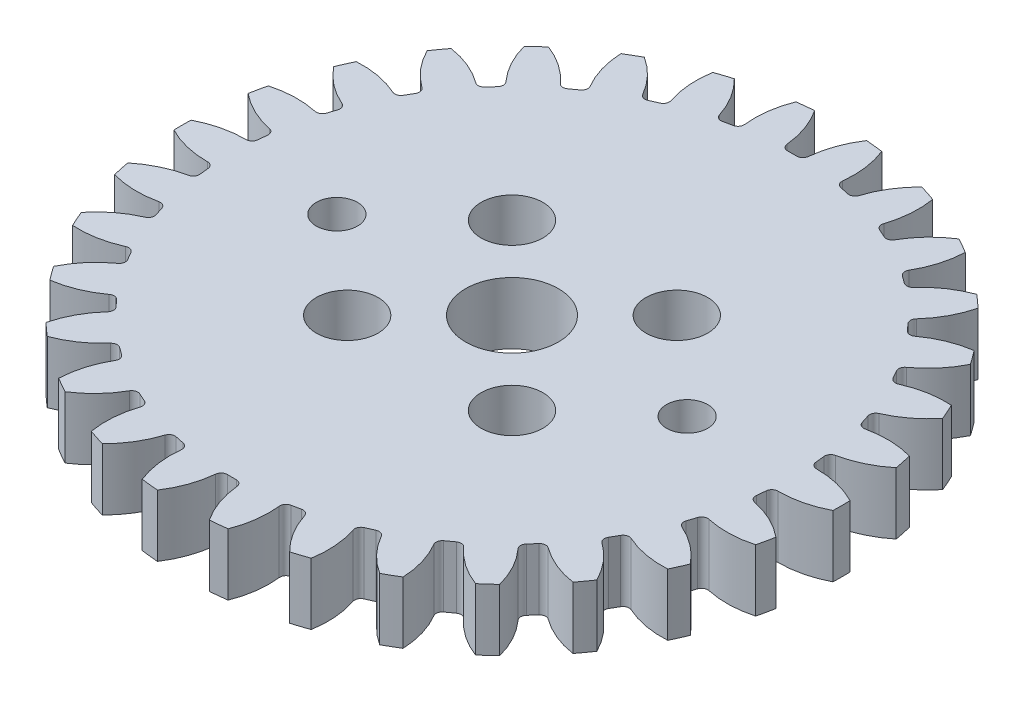
SolidWorks part; units mm, degrees
ref_plane "Alzado" through (0, 0, 0) normal (0, 0, 1) x (1, 0, 0)
ref_plane "Planta" through (0, 0, 0) normal (0, 1, 0) x (1, 0, 0)
ref_plane "Vista lateral" through (0, 0, 0) normal (1, 0, 0) x (0, 0, -1)
sketch "Croquis1" plane through (0, 0, 0) normal (0, 1, 0) x (1, 0, 0)
  line L0 (0, 0) -> (0, 24.4895) construction
  line L1 (-0.2199, 13.6) -> (0.2199, 13.6)
  line L2 (2.6125, 13.3485) -> (3.0427, 13.2571)
  line L3 (5.3308, 12.5136) -> (5.7325, 12.3348)
  line L4 (7.816, 11.1319) -> (8.1718, 10.8734)
  line L5 (9.9596, 9.2636) -> (10.2539, 8.9368)
  line L6 (11.668, 6.9904) -> (11.8879, 6.6096)
  line L7 (12.8664, 4.4117) -> (13.0023, 3.9935)
  line L8 (13.5025, 1.6403) -> (13.5485, 1.2029)
  line L9 (13.5485, -1.2029) -> (13.5025, -1.6403)
  line L10 (13.0023, -3.9935) -> (12.8664, -4.4117)
  line L11 (11.8879, -6.6096) -> (11.668, -6.9904)
  line L12 (10.2539, -8.9368) -> (9.9596, -9.2636)
  line L13 (8.1718, -10.8734) -> (7.816, -11.1319)
  line L14 (5.7325, -12.3348) -> (5.3308, -12.5136)
  line L15 (3.0427, -13.2571) -> (2.6125, -13.3485)
  line L16 (0.2199, -13.6) -> (-0.2199, -13.6)
  line L17 (-2.6125, -13.3485) -> (-3.0427, -13.2571)
  line L18 (-5.3308, -12.5136) -> (-5.7325, -12.3348)
  line L19 (-7.816, -11.1319) -> (-8.1718, -10.8734)
  line L20 (-9.9596, -9.2636) -> (-10.2539, -8.9368)
  line L21 (-11.668, -6.9904) -> (-11.8879, -6.6096)
  line L22 (-12.8664, -4.4117) -> (-13.0023, -3.9935)
  line L23 (-13.5025, -1.6403) -> (-13.5485, -1.2029)
  line L24 (-13.5485, 1.2029) -> (-13.5025, 1.6403)
  line L25 (-13.0023, 3.9935) -> (-12.8664, 4.4117)
  line L26 (-11.8879, 6.6096) -> (-11.668, 6.9904)
  line L27 (-10.2539, 8.9368) -> (-9.9596, 9.2636)
  line L28 (-8.1718, 10.8734) -> (-7.816, 11.1319)
  line L29 (-5.7325, 12.3348) -> (-5.3308, 12.5136)
  line L30 (-3.0427, 13.2571) -> (-2.6125, 13.3485)
  line L31 (0, 0) -> (0, -0.9994) construction
  line L32 (0, 0) -> (10.2539, 0) construction
  circle A0 centre (0, 0) radius 16
  arc A1 (0.5184, 13.8707) -> (2.08, 16.88) centre (5.0567, 13.4256) cw
  arc A2 (-0.5184, 13.8707) -> (-2.08, 16.88) centre (-5.0567, 13.4256) ccw
  arc A3 (-2.08, 16.88) -> (2.08, 16.88) centre (0, -0.9994) cw
  arc A4 (0.2199, 13.6) -> (0.5184, 13.8707) centre (0.2199, 13.9) ccw
  arc A5 (-0.5184, 13.8707) -> (-0.2199, 13.6) centre (-0.2199, 13.9) ccw
  arc A6 (1.475, 16.9436) -> (5.5441, 16.0787) centre (-0.2078, -0.9776) cw
  arc A7 (3.391, 13.4598) -> (5.5441, 16.0787) centre (7.7375, 12.0809) cw
  arc A8 (3.0427, 13.2571) -> (3.391, 13.4598) centre (3.105, 13.5505) ccw
  arc A9 (2.3768, 13.6754) -> (2.6125, 13.3485) centre (2.6749, 13.642) ccw
  arc A10 (2.3768, 13.6754) -> (1.475, 16.9436) centre (-2.1548, 14.1835) ccw
  arc A11 (4.9655, 16.2667) -> (8.7659, 14.5746) centre (-0.4065, -0.913) cw
  arc A12 (6.1153, 12.4607) -> (8.7659, 14.5746) centre (10.0802, 10.2081) cw
  arc A13 (5.7325, 12.3348) -> (6.1153, 12.4607) centre (5.8545, 12.6089) ccw
  arc A14 (5.1681, 12.8824) -> (5.3308, 12.5136) centre (5.4528, 12.7877) ccw
  arc A15 (5.1681, 12.8824) -> (4.9655, 16.2667) centre (0.8412, 14.3216) ccw
  arc A16 (8.2391, 14.8788) -> (11.6046, 12.4336) centre (-0.5874, -0.8085) cw
  arc A17 (8.5724, 10.9169) -> (11.6046, 12.4336) centre (11.9823, 7.8893) cw
  arc A18 (8.1718, 10.8734) -> (8.5724, 10.9169) centre (8.3481, 11.1161) ccw
  arc A19 (7.7336, 11.5264) -> (7.816, 11.1319) centre (7.9923, 11.3746) ccw
  arc A20 (7.7336, 11.5264) -> (8.2391, 14.8788) centre (3.8004, 13.8337) ccw
  arc A21 (11.1525, 12.8407) -> (13.9361, 9.7492) centre (-0.7427, -0.6687) cw
  arc A22 (10.6549, 8.896) -> (13.9361, 9.7492) centre (13.3607, 5.2256) cw
  arc A23 (10.2539, 8.9368) -> (10.6549, 8.896) centre (10.4768, 9.1375) ccw
  arc A24 (9.961, 9.6666) -> (9.9596, 9.2636) centre (10.1826, 9.4643) ccw
  arc A25 (9.961, 9.6666) -> (11.1525, 12.8407) centre (6.5936, 12.7413) ccw
  arc A26 (13.5785, 10.2413) -> (15.6585, 6.6387) centre (-0.8655, -0.4997) cw
  arc A27 (12.2716, 6.4864) -> (15.6585, 6.6387) centre (14.1552, 2.3336) cw
  arc A28 (11.8879, 6.6096) -> (12.2716, 6.4864) centre (12.1477, 6.7596) ccw
  arc A29 (11.7532, 7.3843) -> (11.668, 6.9904) centre (11.9278, 7.1404) ccw
  arc A30 (11.7532, 7.3843) -> (13.5785, 10.2413) centre (9.0986, 11.092) ccw
  arc A31 (15.4111, 7.1944) -> (16.6966, 3.238) centre (-0.9505, -0.3088) cw
  arc A32 (13.352, 3.7932) -> (16.6966, 3.238) centre (14.3311, -0.6604) cw
  arc A33 (13.0023, 3.9935) -> (13.352, 3.7932) centre (13.2876, 4.0862) ccw
  arc A34 (13.0316, 4.7794) -> (12.8664, 4.4117) centre (13.1517, 4.5044) ccw
  arc A35 (13.0316, 4.7794) -> (15.4111, 7.1944) centre (11.2059, 8.9579) ccw
  arc A36 (16.5701, 3.833) -> (17.0049, -0.3042) centre (-0.9939, -0.1045) cw
  arc A37 (13.8489, 0.9343) -> (17.0049, -0.3042) centre (13.8806, -3.6256) cw
  arc A38 (13.5485, 1.2029) -> (13.8489, 0.9343) centre (13.8468, 1.2343) ccw
  arc A39 (13.7405, 1.9655) -> (13.5025, 1.6403) centre (13.8009, 1.6716) ccw
  arc A40 (13.7405, 1.9655) -> (16.5701, 3.833) centre (12.8235, 6.4323) ccw
  arc A41 (17.0049, 0.3042) -> (16.5701, -3.833) centre (-0.9939, 0.1045) cw
  arc A42 (13.7405, -1.9655) -> (16.5701, -3.833) centre (12.8235, -6.4323) cw
  arc A43 (13.5025, -1.6403) -> (13.7405, -1.9655) centre (13.8009, -1.6716) ccw
  arc A44 (13.8489, -0.9343) -> (13.5485, -1.2029) centre (13.8468, -1.2343) ccw
  arc A45 (13.8489, -0.9343) -> (17.0049, 0.3042) centre (13.8806, 3.6256) ccw
  arc A46 (16.6966, -3.238) -> (15.4111, -7.1944) centre (-0.9505, 0.3088) cw
  arc A47 (13.0316, -4.7794) -> (15.4111, -7.1944) centre (11.2059, -8.9579) cw
  arc A48 (12.8664, -4.4117) -> (13.0316, -4.7794) centre (13.1517, -4.5044) ccw
  arc A49 (13.352, -3.7932) -> (13.0023, -3.9935) centre (13.2876, -4.0862) ccw
  arc A50 (13.352, -3.7932) -> (16.6966, -3.238) centre (14.3311, 0.6604) ccw
  arc A51 (15.6585, -6.6387) -> (13.5785, -10.2413) centre (-0.8655, 0.4997) cw
  arc A52 (11.7532, -7.3843) -> (13.5785, -10.2413) centre (9.0986, -11.092) cw
  arc A53 (11.668, -6.9904) -> (11.7532, -7.3843) centre (11.9278, -7.1404) ccw
  arc A54 (12.2716, -6.4864) -> (11.8879, -6.6096) centre (12.1477, -6.7596) ccw
  arc A55 (12.2716, -6.4864) -> (15.6585, -6.6387) centre (14.1552, -2.3336) ccw
  arc A56 (13.9361, -9.7492) -> (11.1525, -12.8407) centre (-0.7427, 0.6687) cw
  arc A57 (9.961, -9.6666) -> (11.1525, -12.8407) centre (6.5936, -12.7413) cw
  arc A58 (9.9596, -9.2636) -> (9.961, -9.6666) centre (10.1826, -9.4643) ccw
  arc A59 (10.6549, -8.896) -> (10.2539, -8.9368) centre (10.4768, -9.1375) ccw
  arc A60 (10.6549, -8.896) -> (13.9361, -9.7492) centre (13.3607, -5.2256) ccw
  arc A61 (11.6046, -12.4336) -> (8.2391, -14.8788) centre (-0.5874, 0.8085) cw
  arc A62 (7.7336, -11.5264) -> (8.2391, -14.8788) centre (3.8004, -13.8337) cw
  arc A63 (7.816, -11.1319) -> (7.7336, -11.5264) centre (7.9923, -11.3746) ccw
  arc A64 (8.5724, -10.9169) -> (8.1718, -10.8734) centre (8.3481, -11.1161) ccw
  arc A65 (8.5724, -10.9169) -> (11.6046, -12.4336) centre (11.9823, -7.8893) ccw
  arc A66 (8.7659, -14.5746) -> (4.9655, -16.2667) centre (-0.4065, 0.913) cw
  arc A67 (5.1681, -12.8824) -> (4.9655, -16.2667) centre (0.8412, -14.3216) cw
  arc A68 (5.3308, -12.5136) -> (5.1681, -12.8824) centre (5.4528, -12.7877) ccw
  arc A69 (6.1153, -12.4607) -> (5.7325, -12.3348) centre (5.8545, -12.6089) ccw
  arc A70 (6.1153, -12.4607) -> (8.7659, -14.5746) centre (10.0802, -10.2081) ccw
  arc A71 (5.5441, -16.0787) -> (1.475, -16.9436) centre (-0.2078, 0.9776) cw
  arc A72 (2.3768, -13.6754) -> (1.475, -16.9436) centre (-2.1548, -14.1835) cw
  arc A73 (2.6125, -13.3485) -> (2.3768, -13.6754) centre (2.6749, -13.642) ccw
  arc A74 (3.391, -13.4598) -> (3.0427, -13.2571) centre (3.105, -13.5505) ccw
  arc A75 (3.391, -13.4598) -> (5.5441, -16.0787) centre (7.7375, -12.0809) ccw
  arc A76 (2.08, -16.88) -> (-2.08, -16.88) centre (0, 0.9994) cw
  arc A77 (-0.5184, -13.8707) -> (-2.08, -16.88) centre (-5.0567, -13.4256) cw
  arc A78 (-0.2199, -13.6) -> (-0.5184, -13.8707) centre (-0.2199, -13.9) ccw
  arc A79 (0.5184, -13.8707) -> (0.2199, -13.6) centre (0.2199, -13.9) ccw
  arc A80 (0.5184, -13.8707) -> (2.08, -16.88) centre (5.0567, -13.4256) ccw
  arc A81 (-1.475, -16.9436) -> (-5.5441, -16.0787) centre (0.2078, 0.9776) cw
  arc A82 (-3.391, -13.4598) -> (-5.5441, -16.0787) centre (-7.7375, -12.0809) cw
  arc A83 (-3.0427, -13.2571) -> (-3.391, -13.4598) centre (-3.105, -13.5505) ccw
  arc A84 (-2.3768, -13.6754) -> (-2.6125, -13.3485) centre (-2.6749, -13.642) ccw
  arc A85 (-2.3768, -13.6754) -> (-1.475, -16.9436) centre (2.1548, -14.1835) ccw
  arc A86 (-4.9655, -16.2667) -> (-8.7659, -14.5746) centre (0.4065, 0.913) cw
  arc A87 (-6.1153, -12.4607) -> (-8.7659, -14.5746) centre (-10.0802, -10.2081) cw
  arc A88 (-5.7325, -12.3348) -> (-6.1153, -12.4607) centre (-5.8545, -12.6089) ccw
  arc A89 (-5.1681, -12.8824) -> (-5.3308, -12.5136) centre (-5.4528, -12.7877) ccw
  arc A90 (-5.1681, -12.8824) -> (-4.9655, -16.2667) centre (-0.8412, -14.3216) ccw
  arc A91 (-8.2391, -14.8788) -> (-11.6046, -12.4336) centre (0.5874, 0.8085) cw
  arc A92 (-8.5724, -10.9169) -> (-11.6046, -12.4336) centre (-11.9823, -7.8893) cw
  arc A93 (-8.1718, -10.8734) -> (-8.5724, -10.9169) centre (-8.3481, -11.1161) ccw
  arc A94 (-7.7336, -11.5264) -> (-7.816, -11.1319) centre (-7.9923, -11.3746) ccw
  arc A95 (-7.7336, -11.5264) -> (-8.2391, -14.8788) centre (-3.8004, -13.8337) ccw
  arc A96 (-11.1525, -12.8407) -> (-13.9361, -9.7492) centre (0.7427, 0.6687) cw
  arc A97 (-10.6549, -8.896) -> (-13.9361, -9.7492) centre (-13.3607, -5.2256) cw
  arc A98 (-10.2539, -8.9368) -> (-10.6549, -8.896) centre (-10.4768, -9.1375) ccw
  arc A99 (-9.961, -9.6666) -> (-9.9596, -9.2636) centre (-10.1826, -9.4643) ccw
  arc A100 (-9.961, -9.6666) -> (-11.1525, -12.8407) centre (-6.5936, -12.7413) ccw
  arc A101 (-13.5785, -10.2413) -> (-15.6585, -6.6387) centre (0.8655, 0.4997) cw
  arc A102 (-12.2716, -6.4864) -> (-15.6585, -6.6387) centre (-14.1552, -2.3336) cw
  arc A103 (-11.8879, -6.6096) -> (-12.2716, -6.4864) centre (-12.1477, -6.7596) ccw
  arc A104 (-11.7532, -7.3843) -> (-11.668, -6.9904) centre (-11.9278, -7.1404) ccw
  arc A105 (-11.7532, -7.3843) -> (-13.5785, -10.2413) centre (-9.0986, -11.092) ccw
  arc A106 (-15.4111, -7.1944) -> (-16.6966, -3.238) centre (0.9505, 0.3088) cw
  arc A107 (-13.352, -3.7932) -> (-16.6966, -3.238) centre (-14.3311, 0.6604) cw
  arc A108 (-13.0023, -3.9935) -> (-13.352, -3.7932) centre (-13.2876, -4.0862) ccw
  arc A109 (-13.0316, -4.7794) -> (-12.8664, -4.4117) centre (-13.1517, -4.5044) ccw
  arc A110 (-13.0316, -4.7794) -> (-15.4111, -7.1944) centre (-11.2059, -8.9579) ccw
  arc A111 (-16.5701, -3.833) -> (-17.0049, 0.3042) centre (0.9939, 0.1045) cw
  arc A112 (-13.8489, -0.9343) -> (-17.0049, 0.3042) centre (-13.8806, 3.6256) cw
  arc A113 (-13.5485, -1.2029) -> (-13.8489, -0.9343) centre (-13.8468, -1.2343) ccw
  arc A114 (-13.7405, -1.9655) -> (-13.5025, -1.6403) centre (-13.8009, -1.6716) ccw
  arc A115 (-13.7405, -1.9655) -> (-16.5701, -3.833) centre (-12.8235, -6.4323) ccw
  arc A116 (-17.0049, -0.3042) -> (-16.5701, 3.833) centre (0.9939, -0.1045) cw
  arc A117 (-13.7405, 1.9655) -> (-16.5701, 3.833) centre (-12.8235, 6.4323) cw
  arc A118 (-13.5025, 1.6403) -> (-13.7405, 1.9655) centre (-13.8009, 1.6716) ccw
  arc A119 (-13.8489, 0.9343) -> (-13.5485, 1.2029) centre (-13.8468, 1.2343) ccw
  arc A120 (-13.8489, 0.9343) -> (-17.0049, -0.3042) centre (-13.8806, -3.6256) ccw
  arc A121 (-16.6966, 3.238) -> (-15.4111, 7.1944) centre (0.9505, -0.3088) cw
  arc A122 (-13.0316, 4.7794) -> (-15.4111, 7.1944) centre (-11.2059, 8.9579) cw
  arc A123 (-12.8664, 4.4117) -> (-13.0316, 4.7794) centre (-13.1517, 4.5044) ccw
  arc A124 (-13.352, 3.7932) -> (-13.0023, 3.9935) centre (-13.2876, 4.0862) ccw
  arc A125 (-13.352, 3.7932) -> (-16.6966, 3.238) centre (-14.3311, -0.6604) ccw
  arc A126 (-15.6585, 6.6387) -> (-13.5785, 10.2413) centre (0.8655, -0.4997) cw
  arc A127 (-11.7532, 7.3843) -> (-13.5785, 10.2413) centre (-9.0986, 11.092) cw
  arc A128 (-11.668, 6.9904) -> (-11.7532, 7.3843) centre (-11.9278, 7.1404) ccw
  arc A129 (-12.2716, 6.4864) -> (-11.8879, 6.6096) centre (-12.1477, 6.7596) ccw
  arc A130 (-12.2716, 6.4864) -> (-15.6585, 6.6387) centre (-14.1552, 2.3336) ccw
  arc A131 (-13.9361, 9.7492) -> (-11.1525, 12.8407) centre (0.7427, -0.6687) cw
  arc A132 (-9.961, 9.6666) -> (-11.1525, 12.8407) centre (-6.5936, 12.7413) cw
  arc A133 (-9.9596, 9.2636) -> (-9.961, 9.6666) centre (-10.1826, 9.4643) ccw
  arc A134 (-10.6549, 8.896) -> (-10.2539, 8.9368) centre (-10.4768, 9.1375) ccw
  arc A135 (-10.6549, 8.896) -> (-13.9361, 9.7492) centre (-13.3607, 5.2256) ccw
  arc A136 (-11.6046, 12.4336) -> (-8.2391, 14.8788) centre (0.5874, -0.8085) cw
  arc A137 (-7.7336, 11.5264) -> (-8.2391, 14.8788) centre (-3.8004, 13.8337) cw
  arc A138 (-7.816, 11.1319) -> (-7.7336, 11.5264) centre (-7.9923, 11.3746) ccw
  arc A139 (-8.5724, 10.9169) -> (-8.1718, 10.8734) centre (-8.3481, 11.1161) ccw
  arc A140 (-8.5724, 10.9169) -> (-11.6046, 12.4336) centre (-11.9823, 7.8893) ccw
  arc A141 (-8.7659, 14.5746) -> (-4.9655, 16.2667) centre (0.4065, -0.913) cw
  arc A142 (-5.1681, 12.8824) -> (-4.9655, 16.2667) centre (-0.8412, 14.3216) cw
  arc A143 (-5.3308, 12.5136) -> (-5.1681, 12.8824) centre (-5.4528, 12.7877) ccw
  arc A144 (-6.1153, 12.4607) -> (-5.7325, 12.3348) centre (-5.8545, 12.6089) ccw
  arc A145 (-6.1153, 12.4607) -> (-8.7659, 14.5746) centre (-10.0802, 10.2081) ccw
  arc A146 (-5.5441, 16.0787) -> (-1.475, 16.9436) centre (0.2078, -0.9776) cw
  arc A147 (-2.3768, 13.6754) -> (-1.475, 16.9436) centre (2.1548, 14.1835) cw
  arc A148 (-2.6125, 13.3485) -> (-2.3768, 13.6754) centre (-2.6749, 13.642) ccw
  arc A149 (-3.391, 13.4598) -> (-3.0427, 13.2571) centre (-3.105, 13.5505) ccw
  arc A150 (-3.391, 13.4598) -> (-5.5441, 16.0787) centre (-7.7375, 12.0809) ccw
  circle A151 centre (4, 4) radius 1.5
  circle A152 centre (-4, 4) radius 1.5
  circle A153 centre (4, -4) radius 1.5
  circle A154 centre (-4, -4) radius 1.5
  circle A155 centre (-8.5, 0) radius 1
  circle A156 centre (8.5, 0) radius 1
  circle A157 centre (0, 0) radius 2.25
  point P11 (0, 13.6)
  point P14 (0.5, 13.6)
  point P17 (-0.5, 13.6)
  dimension "D1" = 32
  dimension "D6" = 4.56
  dimension "D7" = 18
  dimension "D8" = 0.3
  dimension "D11" = 7.2115
  dimension "D12" = 3
  dimension "D15" = 2
  dimension "D17" = 4.5
  dimension "D2" = 0.5
  dimension "D3" = 13.6
  dimension "D4" = 1.58
  dimension "D5" = 3.28
  dimension "D10" = 0.9994
  dimension "D13" = 4
  dimension "D14" = 4
  dimension "D16" = 8.5
  dimension "D9" = 30
extrude "Saliente-Extruir1" add sketch "Croquis1" along normal blind 3 contours A149 A150 A0 A142 A143 L29 A144 A145 A137 A138 L28 A139 A140 A132 A133 L27 A134 A135 A127 A128 L26 A129 A130 A122 A123 L25 A124 A125 A117 A118 L24 A119 A120 A112 A113 L23 A114 A115 A107 A108 L22 A109 A110
